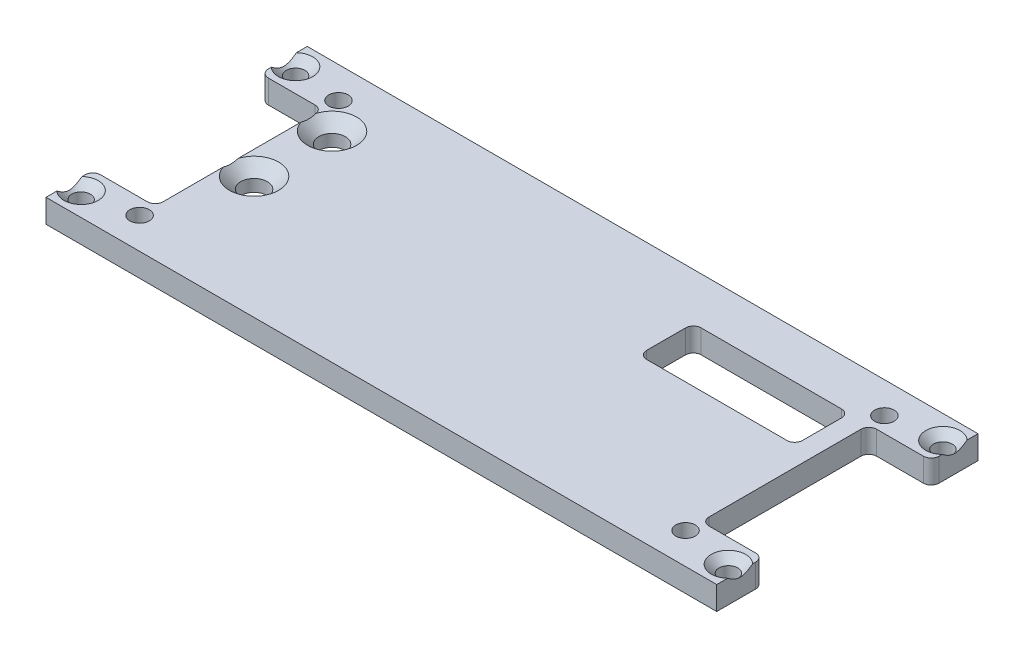
SolidWorks part; units mm, degrees
material "6063-T5"
ref_plane "Front Plane" through (0, 0, 0) normal (0, 0, 1) x (1, 0, 0)
ref_plane "Top Plane" through (0, 0, 0) normal (0, 1, 0) x (1, 0, 0)
ref_plane "Right Plane" through (0, 0, 0) normal (1, 0, 0) x (0, 0, -1)
sketch "Sketch1" plane through (0, 0, 0) normal (0, 1, 0) x (1, 0, 0)
  line L1 (-43, -16.75) -> (43, -16.75)
  line L2 (-43, -16.75) -> (-43, 16.75)
  line L3 (-43, 16.75) -> (43, 16.75)
  line L4 (43, -16.75) -> (43, 16.75)
  line L5 (-43, -16.75) -> (43, 16.75) construction
  line L6 (-43, 16.75) -> (43, -16.75) construction
  line L7 (32.5, 3.75) -> (12.5, 3.75)
  line L8 (32.5, 3.75) -> (32.5, 10.75)
  line L9 (32.5, 10.75) -> (12.5, 10.75)
  line L10 (12.5, 3.75) -> (12.5, 10.75)
  point P0 (0, 0)
  point P10 (32.5, 7.25)
  dimension "D1" = 33.5
  dimension "D2" = 86
  dimension "D3" = 10.5
  dimension "D4" = 6
  dimension "D5" = 7
  dimension "D6" = 20
extrude "Boss-Extrude1" add sketch "Sketch1" along normal mid plane 3
sketch "Sketch2" plane through (0, -1.5, 0) normal (0, 1, 0) x (1, 0, 0)
  line L5 (-43, 16.75) -> (-43, -16.75) construction
  line L6 (-34.5, -4.8195) -> (-31.5, -4.8195)
  line L8 (-34.5, -4.8195) -> (-34.5, 12.6805)
  line L9 (-34.5, 12.6805) -> (-31.5, 12.6805)
  line L10 (-31.5, -4.8195) -> (-31.5, 12.6805)
  line L13 (-43, -16.75) -> (43, -16.75) construction
  dimension "D1" = 3
  dimension "D2" = 8.5
  dimension "D3" = 17.5
  dimension "D4" = 11.9305
hole_wizard "CSK for M3 Countersunk Flat Head Screw1" positions "Sketch19" profile "Sketch20" countersink size "M3" standard "DIN"
sketch "Sketch19" plane through (0, 1.5, 0) normal (0, 1, 0) x (1, 0, 0)
  line L0 (43, 16.75) -> (-43, 16.75) construction
  line L1 (-43, 16.75) -> (-43, -16.75) construction
  point P0 (-32, 8.9305)
  point P2 (-32, -1.0695)
  dimension "D1" = 10
  dimension "D2" = 7.8195
  dimension "D3" = 11
sketch "Sketch20" plane through (-32, 1.5, -8.9305) normal (1, 0, 0) x (0, 0, 1)
  line L0 (0, 0) -> (0, 7.0215)
  line L1 (0, 7.0215) -> (1.7, 6)
  line L2 (1.7, 6) -> (1.7, 1.45)
  line L3 (1.7, 1.45) -> (3.15, 0)
  line L5 (3.15, 0) -> (0, 0)
  line L6 (-1.7, 1.45) -> (-3.15, 0) construction
  line L10 (0, 7.0215) -> (-1.7, 6) construction
  line L11 (0, -6.35) -> (0, 107.95) construction
  dimension "Hole Dia." = 3.4
  dimension "Hole Depth" = 6
  dimension "Near C'Sink Dia." = 6.3
  dimension "Near C'Sink Angle" = 90
  dimension "Drill Angle" = 118
hole_wizard "Tap Drill for M3 Tap1" positions "Sketch5" profile "Sketch6" hole size "M3" standard "ISO" end condition through all
sketch "Sketch5" plane through (0, 1.5, 0) normal (0, 1, 0) x (1, 0, 0)
  line L0 (-43, -16.75) -> (43, -16.75) construction
  line L3 (43, 16.75) -> (-43, 16.75) construction
  line L4 (0, -1.7279) -> (0, 1.7279) construction
  point P0 (-35, 12.75)
  point P2 (-35, -12.75)
  point P4 (35, -12.75)
  point P6 (35, 12.75)
  dimension "D1" = 4
  dimension "D2" = 35
  dimension "D3" = 70
  dimension "D4" = 4
sketch "Sketch6" plane through (-35, 1.5, -12.75) normal (1, 0, 0) x (0, 0, 1)
  line L0 (0, 0) -> (0, 3)
  line L1 (0, 3) -> (1.25, 3)
  line L2 (1.25, 3) -> (1.25, 0)
  line L5 (1.25, 0) -> (0, 0)
  line L11 (0, -6.35) -> (0, 107.95) construction
  dimension "Thru Hole Dia." = 2.5
  dimension "Thru Hole Depth" = 3
cosmetic thread "Cosmetic Thread1" parameters "D2"=3
cosmetic thread "Cosmetic Thread2" parameters "D2"=3
cosmetic thread "Cosmetic Thread3" parameters "D2"=3
cosmetic thread "Cosmetic Thread4" parameters "D2"=3
extrude "Boss-Extrude2" [suppressed] add sketch "Sketch2" against normal blind 23.5
hole_wizard "CSK for M2 Countersunk Flat Head Screw2" [suppressed] positions "Sketch9" profile "Sketch10" countersink size "M2" standard "ISO"
sketch "Sketch9" [suppressed] plane through (-34.5, 0, 0) normal (-1, 0, 0) x (0, 0, 1)
  line L0 (-12.6805, -25) -> (-12.6805, -1.5) construction
  line L1 (-12.6805, -25) -> (4.8195, -25) construction
  circle A0 centre (-3.78, -14.78) radius 6 construction
  point P0 (-3.78, -20.78)
  point P19 (-8.9761, -11.78)
  point P20 (1.4162, -11.78)
  dimension "D1" = 12
  dimension "D2" = 8.9006
  dimension "D3" = 10.22
  dimension "D4" = 3
sketch "Sketch10" plane through (-34.5, -20.78, -3.78) normal (0, 1, 0) x (0, 0, 1)
  line L0 (0, 0) -> (0, 5.7811)
  line L1 (0, 5.7811) -> (1.3, 5)
  line L2 (1.3, 5) -> (1.3, 0.9)
  line L3 (1.3, 0.9) -> (2.2, 0)
  line L5 (2.2, 0) -> (0, 0)
  line L6 (-1.3, 0.9) -> (-2.2, 0) construction
  line L10 (0, 5.7811) -> (-1.3, 5) construction
  line L11 (0, -6.35) -> (0, 107.95) construction
  dimension "Hole Dia." = 2.6
  dimension "Hole Depth" = 5
  dimension "Near C'Sink Dia." = 4.4
  dimension "Near C'Sink Angle" = 90
  dimension "Drill Angle" = 118
sketch "Sketch11" [suppressed] plane through (-34.5, 0, 0) normal (-1, 0, 0) x (0, 0, 1)
  line L2 (-12.6805, -1.5) -> (4.8195, -1.5) construction
  line L3 (-8.9305, -1.5) -> (1.0695, -1.5) construction
  line L5 (4.8195, -25) -> (4.8195, -1.5) construction
  line L6 (4.8195, -7.5) -> (-12.6805, -7.5) construction
  line L7 (-12.6805, -7.5) -> (-12.6805, -1.5)
  line L8 (-12.6805, -1.5) -> (-8.9305, -1.5)
  line L9 (-8.9305, -1.5) -> (-8.9305, -7.5)
  line L11 (1.0695, -1.5) -> (4.8195, -1.5)
  line L12 (4.8195, -1.5) -> (4.8195, -7.5)
  line L13 (1.0695, -1.5) -> (1.0695, -7.5)
  line L15 (-12.6805, -25) -> (-12.6805, -1.5) construction
  line L16 (-8.9305, -7.5) -> (-12.6805, -7.5)
  line L17 (1.0695, -7.5) -> (4.8195, -7.5)
  dimension "D1" = 10
  dimension "D2" = 6
extrude "Cut-Extrude1" [suppressed] cut sketch "Sketch11" against normal up to next
ref_plane "Plane1" [suppressed] through (0, 0, -3.9305) normal (0, 0, -1) x (-1, 0, 0)
sketch "Sketch12" [suppressed] plane through (-34.5, 0, 0) normal (-1, 0, 0) x (0, 0, 1)
  circle A0 centre (-3.78, -14.78) radius 3.5
  circle A4 centre (-3.78, -14.78) radius 6 construction
  point P2 (-8.9761, -11.78)
  point P3 (1.4162, -11.78)
  point P4 (-3.78, -20.78)
  dimension "D1" = 7
extrude "Cut-Extrude2" [suppressed] cut sketch "Sketch12" against normal up to next
fillet "Fillet1" [suppressed] radius 5
chamfer "Chamfer1" [suppressed] distance 3 distance2 10
chamfer "Chamfer2" [suppressed] distance 2 angle 45
ref_plane "Plane2" through (0, -11.5, 0) normal (0, -1, 0) x (-1, 0, 0)
sketch "Sketch13" plane through (0, -11.5, 0) normal (0, -1, 0) x (1, 0, 0)
  line L1 (-40, 8.75) -> (-36.5, 8.75)
  line L2 (-40, 8.75) -> (-40, -9.25)
  line L3 (-40, -9.25) -> (-36.5, -9.25)
  line L4 (-36.5, 8.75) -> (-36.5, -9.25)
  line L5 (-43, -16.75) -> (-43, 16.75) construction
  line L7 (-43, 16.75) -> (43, 16.75) construction
  dimension "D1" = 18
  dimension "D2" = 3
  dimension "D3" = 3.5
  dimension "D4" = 8
extrude "Cut-Extrude3" cut sketch "Sketch13" against normal through all
sketch "Sketch14" [suppressed] plane through (0, 1.5, 0) normal (0, 1, 0) x (1, 0, 0)
  line L1 (-38.5, -15.25) -> (-34.5, -15.25)
  line L2 (-38.5, -15.25) -> (-38.5, -11.25)
  line L3 (-38.5, -11.25) -> (-34.5, -11.25)
  line L4 (-34.5, -15.25) -> (-34.5, -11.25)
  line L5 (-38.5, -15.25) -> (-34.5, -11.25) construction
  line L6 (-38.5, -11.25) -> (-34.5, -15.25) construction
  line L7 (-38.5, 11.25) -> (-34.5, 11.25)
  line L8 (-38.5, 11.25) -> (-38.5, 15.25)
  line L9 (-38.5, 15.25) -> (-34.5, 15.25)
  line L10 (-34.5, 11.25) -> (-34.5, 15.25)
  line L11 (-38.5, 11.25) -> (-34.5, 15.25) construction
  line L12 (-38.5, 15.25) -> (-34.5, 11.25) construction
  line L13 (34.5, 11.25) -> (38.5, 11.25)
  line L14 (34.5, 11.25) -> (34.5, 15.25)
  line L15 (34.5, 15.25) -> (38.5, 15.25)
  line L16 (38.5, 11.25) -> (38.5, 15.25)
  line L17 (34.5, 11.25) -> (38.5, 15.25) construction
  line L18 (34.5, 15.25) -> (38.5, 11.25) construction
  line L19 (34.5, -15.25) -> (38.5, -15.25)
  line L20 (34.5, -15.25) -> (34.5, -11.25)
  line L21 (34.5, -11.25) -> (38.5, -11.25)
  line L22 (38.5, -15.25) -> (38.5, -11.25)
  line L23 (34.5, -15.25) -> (38.5, -11.25) construction
  line L24 (34.5, -11.25) -> (38.5, -15.25) construction
  circle A0 centre (-36.5, 13.25) radius 1.2
  circle A1 centre (36.5, 13.25) radius 1.2
  circle A2 centre (36.5, -13.25) radius 1.2
  circle A3 centre (-36.5, -13.25) radius 1.2
  circle A4 centre (-36.5, -13.25) radius 1.2 construction
  point P0 (-36.5, -13.25)
  point P6 (-36.5, 13.25)
  point P12 (36.5, 13.25)
  point P18 (36.5, -13.25)
  dimension "D1" = 4
extrude "Boss-Extrude3" [suppressed] add sketch "Sketch14" along normal blind 0.5
hole_wizard "CSK for M2 Countersunk Flat Head Screw3" positions "Sketch15" profile "Sketch16" countersink size "M2" standard "ISO"
sketch "Sketch15" plane through (0, 1.5, 0) normal (0, 1, 0) x (1, 0, 0)
  line L0 (-43, 16.75) -> (-43, -16.75) construction
  line L1 (43, -16.75) -> (43, 16.75) construction
  line L2 (43, 16.75) -> (-43, 16.75) construction
  line L3 (-43, -16.75) -> (43, -16.75) construction
  point P0 (-41.5, -13.75)
  point P2 (-41.5, 13.75)
  point P4 (41.5, 13.75)
  point P6 (41.5, -13.75)
  dimension "D1" = 1.5
  dimension "D2" = 1.5
  dimension "D3" = 3
  dimension "D4" = 3
sketch "Sketch16" plane through (-41.5, 1.5, 13.75) normal (1, 0, 0) x (0, 0, 1)
  line L0 (0, 0) -> (0, 4.721)
  line L1 (0, 4.721) -> (1.2, 4)
  line L2 (1.2, 4) -> (1.2, 1)
  line L3 (1.2, 1) -> (2.2, 0)
  line L5 (2.2, 0) -> (0, 0)
  line L6 (-1.2, 1) -> (-2.2, 0) construction
  line L10 (0, 4.721) -> (-1.2, 4) construction
  line L11 (0, -6.35) -> (0, 107.95) construction
  dimension "Hole Dia." = 2.4
  dimension "Hole Depth" = 4
  dimension "Near C'Sink Dia." = 4.4
  dimension "Near C'Sink Angle" = 90
  dimension "Drill Angle" = 118
sketch "Sketch21" plane through (0, 1.5, 0) normal (0, 1, 0) x (1, 0, 0)
  line L0 (-43, 12.1407) -> (-43, -12.1407) construction
  line L1 (-35, 10.75) -> (-43, 10.75)
  line L2 (-35, 10.75) -> (-35, -10.75)
  line L3 (-35, -10.75) -> (-43, -10.75)
  line L4 (-43, 10.75) -> (-43, -10.75)
  line L5 (0, -1.7279) -> (0, 1.7279) construction
  line L6 (43, 10.75) -> (43, -10.75)
  line L7 (35, -10.75) -> (43, -10.75)
  line L8 (35, 10.75) -> (35, -10.75)
  line L9 (35, 10.75) -> (43, 10.75)
  circle A0 centre (-41.5, 13.75) radius 1.2 construction
  circle A1 centre (-41.5, -13.75) radius 1.2 construction
  dimension "D1" = 8
  dimension "D2" = 3
  dimension "D3" = 3
extrude "Cut-Extrude4" cut sketch "Sketch21" against normal through all
fillet "Fillet2" radius 1 12 edges at (35, 0, 10.75) (43, 0, 10.75) (43, 0, -10.75) (35, 0, -10.75) (-43, 0, 10.75) (-35, 0, 10.75) (-43, 0, -10.75) (-35, 0, -10.75) (12.5, 0, -3.75) (32.5, 0, -3.75) (32.5, 0, -10.75) (12.5, 0, -10.75)
